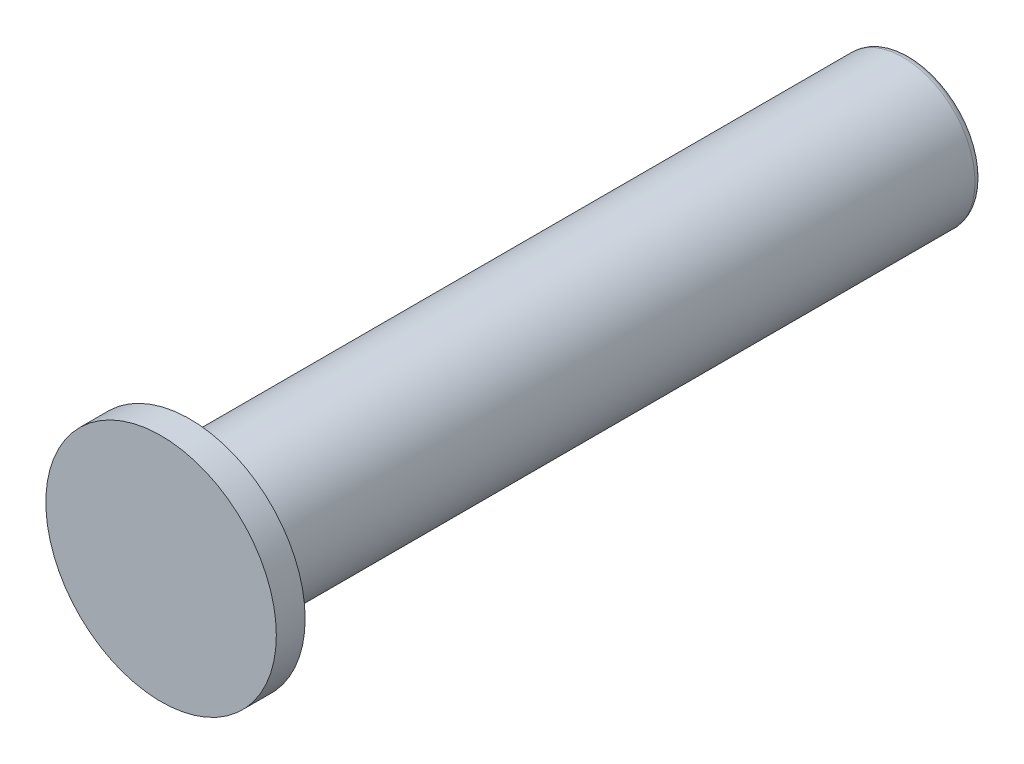
SolidWorks part; units mm, degrees
material "AISI Type A2 Tool Steel"
ref_plane "Front Plane" through (0, 0, 0) normal (0, 0, 1) x (1, 0, 0)
ref_plane "Top Plane" through (0, 0, 0) normal (0, 1, 0) x (1, 0, 0)
ref_plane "Right Plane" through (0, 0, 0) normal (1, 0, 0) x (0, 0, -1)
sketch "Sketch1" plane through (0, 0, 0) normal (0, 0, 1) x (1, 0, 0)
  circle A1 centre (0, 0) radius 5
  dimension "D1" = 10
extrude "Boss-Extrude1" add sketch "Sketch1" along direction (0, 0, 1) on the side of the normal mid plane 50 contours A1
fillet "Fillet3" radius 0.5 1 edges at (5, 0, -25)
sketch "Sketch2" plane through (0, 0, 0) normal (0, 0, 1) x (1, 0, 0)
  circle A0 centre (0, 0) radius 8
  dimension "D1" = 16
extrude "Boss-Extrude2" add sketch "Sketch2" along normal blind 2 from surface at 25 contours A0 starting at face at (5, 0, 25)
